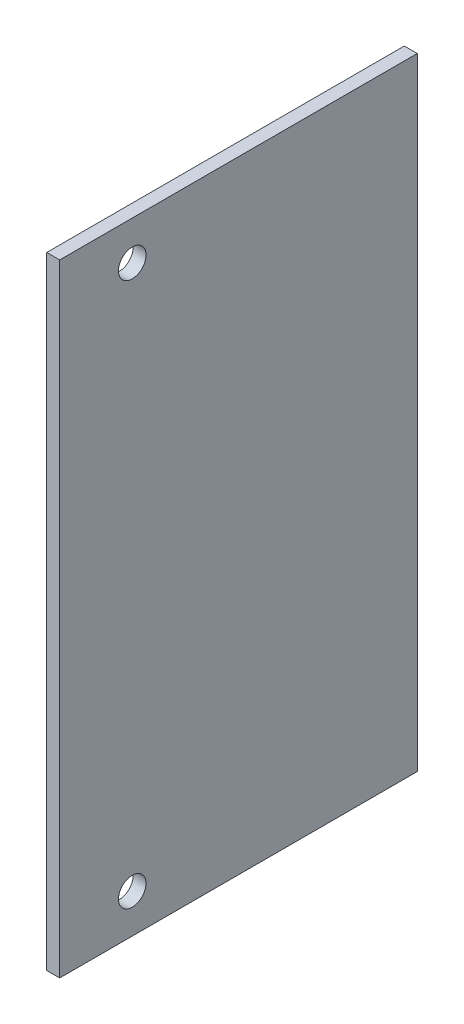
SolidWorks part; units mm, degrees
material "Acrylic (Medium-high impact)"
ref_plane "Front" through (0, 0, 0) normal (0, 0, 1) x (1, 0, 0)
ref_plane "Top" through (0, 0, 0) normal (0, 1, 0) x (1, 0, 0)
ref_plane "Right" through (0, 0, 0) normal (1, 0, 0) x (0, 0, -1)
sketch "Sketch1" plane through (0, 0, 0) normal (1, 0, 0) x (0, 0, -1)
  line L1 (0, 0) -> (87.63, 0)
  line L2 (0, 0) -> (0, 152.4)
  line L3 (0, 152.4) -> (87.63, 152.4)
  line L4 (87.63, 0) -> (87.63, 152.4)
  dimension "D1" = 152.4
  dimension "D2" = 87.63
extrude "Boss-Extrude1" add sketch "Sketch1" along normal blind 3.175
hole_wizard "1/4 Clearance Hole1" positions "Sketch4" profile "Sketch5" hole size "1/4" standard "ANSI Inch" end condition up to next
sketch "Sketch4" plane through (3.175, 0, 0) normal (1, 0, 0) x (0, 0, -1)
  line L0 (17.78, 152.4) -> (17.78, 142.875) construction
  line L1 (87.63, 152.4) -> (0, 152.4) construction
  line L2 (17.78, 142.875) -> (0, 142.875) construction
  line L3 (0, 152.4) -> (0, 0) construction
  line L5 (17.78, 0) -> (17.78, 9.525) construction
  line L6 (0, 0) -> (87.63, 0) construction
  line L7 (17.78, 9.525) -> (0, 9.525) construction
  point P0 (17.78, 142.875)
  point P2 (17.78, 9.525)
  dimension "D1" = 17.78
  dimension "D2" = 9.525
sketch "Sketch5" plane through (3.175, 142.875, -17.78) normal (0, 1, 0) x (0, 0, -1)
  line L0 (0, 0) -> (0, 3.175)
  line L1 (0, 3.175) -> (3.3782, 3.175)
  line L2 (3.3782, 3.175) -> (3.3782, 0)
  line L5 (3.3782, 0) -> (0, 0)
  line L11 (0, -6.35) -> (0, 107.95) construction
  dimension "Thru Hole Dia." = 6.7564
  dimension "Thru Hole Depth" = 3.175
